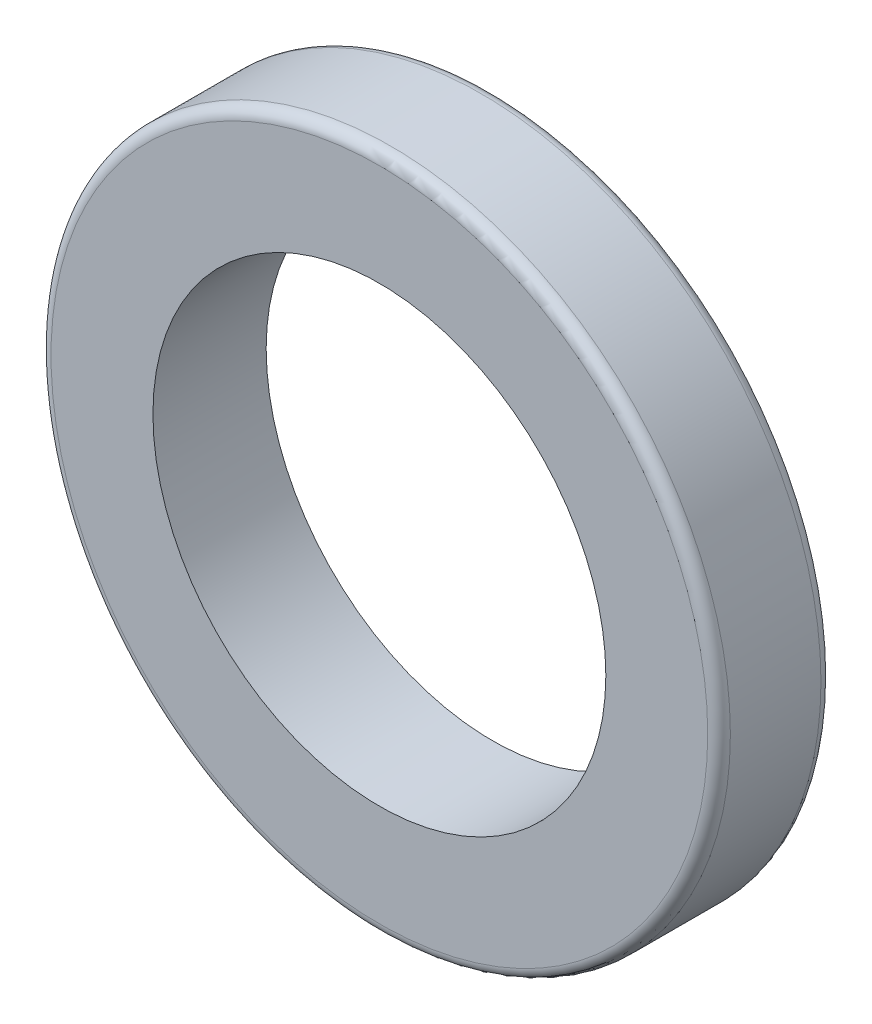
SolidWorks part; units mm, degrees
ref_plane "Front Plane" through (0, 0, 0) normal (0, 0, 1) x (1, 0, 0)
ref_plane "Top Plane" through (0, 0, 0) normal (0, 1, 0) x (1, 0, 0)
ref_plane "Right Plane" through (0, 0, 0) normal (1, 0, 0) x (0, 0, -1)
sketch "Sketch1" plane through (0, 0, 0) normal (0, 0, 1) x (1, 0, 0)
  circle A0 centre (0, 0) radius 5.08
  circle A1 centre (0, 0) radius 7.62
  dimension "D1" = 10.16
  dimension "D2" = 15.24
extrude "Boss-Extrude1" add sketch "Sketch1" along normal blind 2.54
fillet "Fillet1" radius 0.254 2 edges at (7.62, 0, 0) (7.62, 0, 2.54)
